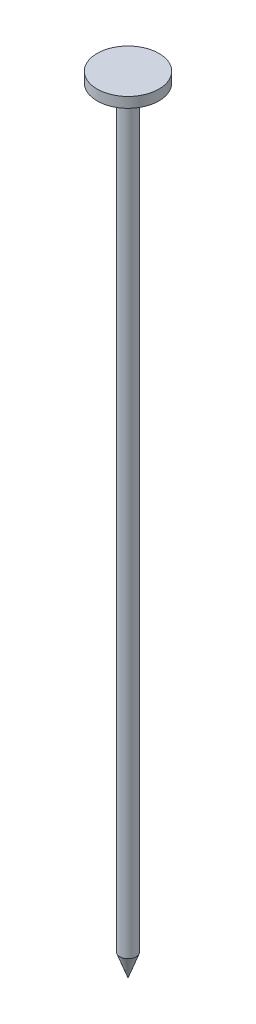
SolidWorks part; units mm, degrees
ref_plane "Front Plane" through (0, 0, 0) normal (0, 0, 1) x (1, 0, 0)
ref_plane "Top Plane" through (0, 0, 0) normal (0, 1, 0) x (1, 0, 0)
ref_plane "Right Plane" through (0, 0, 0) normal (1, 0, 0) x (0, 0, -1)
sketch "Sketch1" plane through (0, 0, 0) normal (0, 0, 1) x (1, 0, 0)
  line L0 (0, 1) -> (3, 1)
  line L1 (3, 1) -> (3, 0)
  line L2 (3, 0) -> (0.7938, 0)
  line L3 (0.7938, 0) -> (0.7938, -73.0192)
  line L4 (0.7938, -73.0192) -> (0, -75.2)
  line L5 (0, -75.2) -> (0, 1)
  dimension "D1" = 76.2
  dimension "D2" = 0.7937
  dimension "D3" = 20
  dimension "D4" = 1
  dimension "D5" = 3
revolve "Revolve1" add sketch "Sketch1" angle 360 about L5
